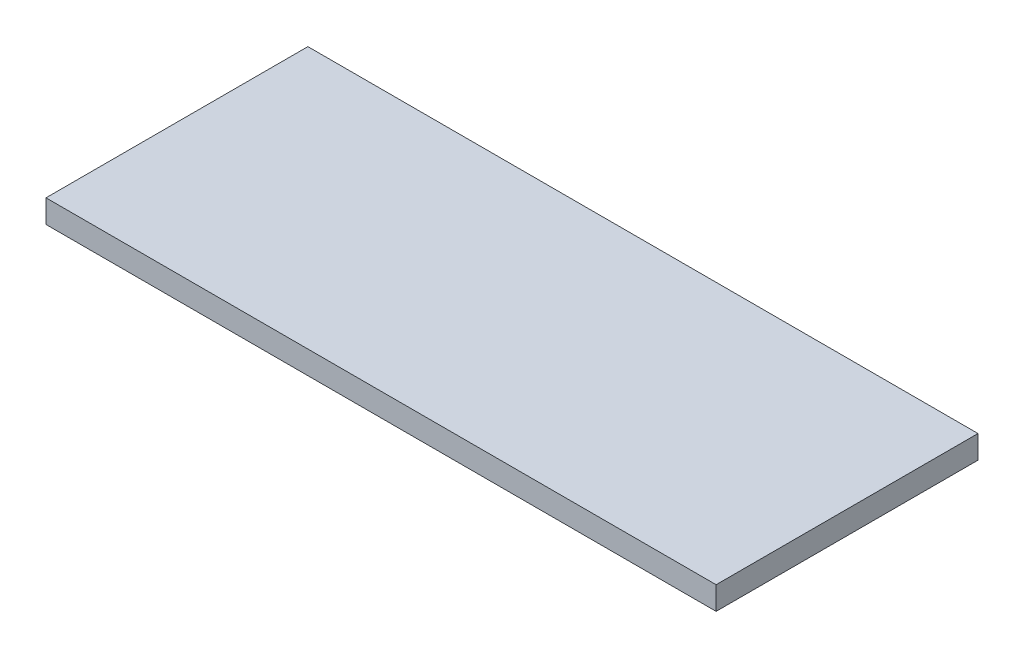
SolidWorks part; units mm, degrees
ref_plane "Front Plane" through (0, 0, 0) normal (0, 0, 1) x (1, 0, 0)
ref_plane "Top Plane" through (0, 0, 0) normal (0, 1, 0) x (1, 0, 0)
ref_plane "Right Plane" through (0, 0, 0) normal (1, 0, 0) x (0, 0, -1)
sketch "Sketch1" plane through (0, 0, 0) normal (0, 1, 0) x (1, 0, 0)
  line L1 (0, 0) -> (552.45, 0)
  line L2 (0, 0) -> (0, 215.9)
  line L3 (0, 215.9) -> (552.45, 215.9)
  line L4 (552.45, 0) -> (552.45, 215.9)
  line L5 (0, 0) -> (552.45, 215.9) construction
  line L6 (0, 215.9) -> (552.45, 0) construction
  point P4 (276.225, 107.95)
  dimension "D1" = 552.45
  dimension "D2" = 215.9
extrude "Boss-Extrude1" add sketch "Sketch1" along normal blind 19.05
